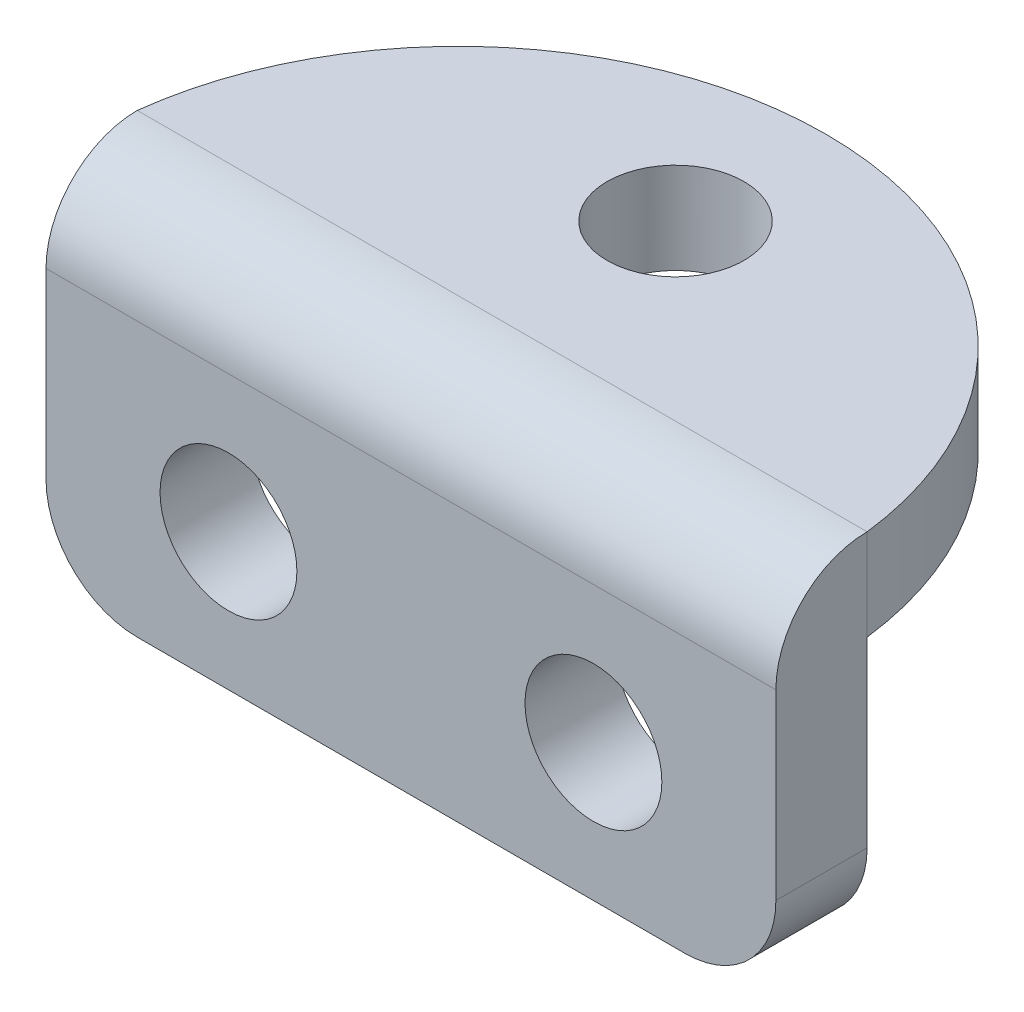
SolidWorks part; units mm, degrees
ref_plane "Front Plane" through (0, 0, 0) normal (0, 0, 1) x (1, 0, 0)
ref_plane "Top Plane" through (0, 0, 0) normal (0, 1, 0) x (1, 0, 0)
ref_plane "Right Plane" through (0, 0, 0) normal (1, 0, 0) x (0, 0, -1)
sketch "Sketch1" plane through (0, 0, 0) normal (0, 0, 1) x (1, 0, 0)
  line L0 (0, 0) -> (0, -4)
  line L1 (2, -6) -> (14, -6)
  line L2 (16, -4) -> (16, 0)
  line L3 (16, 0) -> (0, 0)
  arc A0 (0, -4) -> (2, -6) centre (2, -4) ccw
  arc A1 (16, -4) -> (14, -6) centre (14, -4) cw
  dimension "D1" = 4
  dimension "D4" = 2
  dimension "D2" = 12
  dimension "D3" = 16
  dimension "D5" = 4
extrude "Boss-Extrude1" add sketch "Sketch1" along normal blind 2
sketch "Sketch5" plane through (0, 0, 0) normal (0, 1, 0) x (1, 0, 0)
  line L0 (0, 0) -> (16, 0)
  arc A1 (0, 0) -> (16, 0) centre (8, -0.9598) cw
extrude "Boss-Extrude2" add sketch "Sketch5" along normal blind 2 separate body
sketch "Sketch10" plane through (0, 0, 0) normal (0, 0, -1) x (-1, 0, 0)
  line L0 (-16, -4) -> (-16, 0) construction
  line L1 (0, 0) -> (0, -4) construction
  line L2 (-2, -6) -> (-14, -6) construction
  circle A0 centre (-12, -3) radius 1.5
  circle A1 centre (-4, -3) radius 1.5
  dimension "D1" = 3
  dimension "D2" = 3
  dimension "D3" = 4
  dimension "D4" = 4
  dimension "D5" = 3
  dimension "D6" = 3
extrude "Cortar-Extruir1" cut sketch "Sketch10" against normal blind 10
sketch "Croquis1" plane through (0, 2, 0) normal (0, 1, 0) x (1, 0, 0)
  circle A0 centre (8, 3.8) radius 1.5
extrude "Cortar-Extruir2" cut sketch "Croquis1" against normal blind 10
sketch "Croquis2" plane through (0, 0, 0) normal (-1, 0, 0) x (0, 0, 1)
  line L0 (2, 0) -> (0, 0)
  line L1 (0, 0) -> (0, 2)
  arc A0 (2, 0) -> (0, 2) centre (0, 0) ccw
extrude "Saliente-Extruir1" add sketch "Croquis2" against normal blind 16
